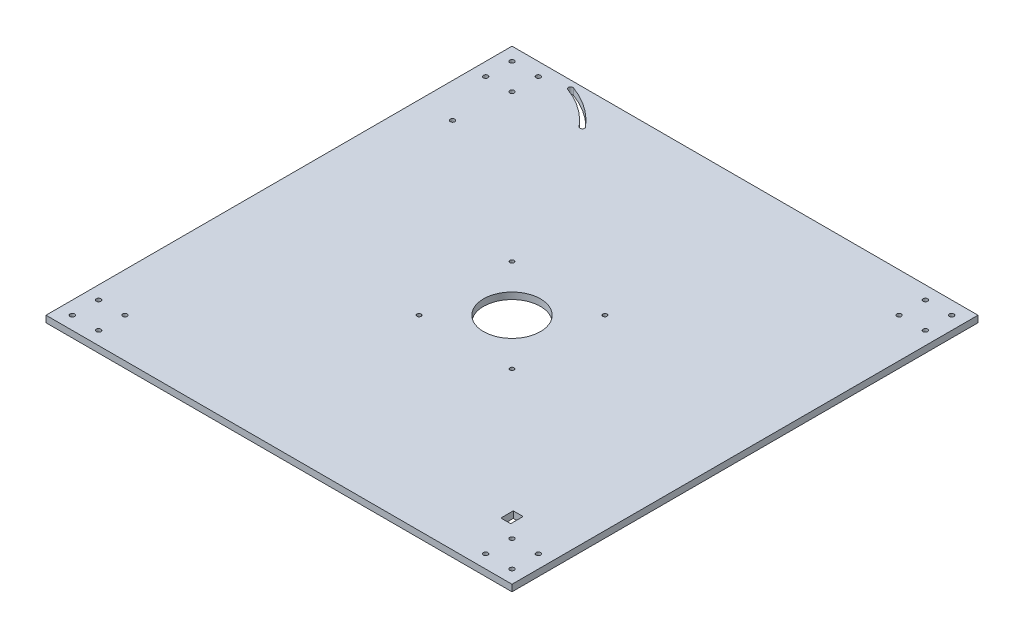
SolidWorks part; units mm, degrees
ref_plane "Front Plane" through (0, 0, 0) normal (0, 0, 1) x (1, 0, 0)
ref_plane "Top Plane" through (0, 0, 0) normal (0, 1, 0) x (1, 0, 0)
ref_plane "Right Plane" through (0, 0, 0) normal (1, 0, 0) x (0, 0, -1)
sketch "Sketch1" plane through (0, 0, 0) normal (0, 1, 0) x (1, 0, 0)
  line L1 (-224.79, -224.79) -> (224.79, -224.79)
  line L2 (-224.79, -224.79) -> (-224.79, 224.79)
  line L3 (-224.79, 224.79) -> (224.79, 224.79)
  line L4 (224.79, -224.79) -> (224.79, 224.79)
  line L5 (-224.79, -224.79) -> (224.79, 224.79) construction
  line L6 (-224.79, 224.79) -> (224.79, -224.79) construction
  point P0 (0, 0)
  dimension "D1" = 449.58
  dimension "D2" = 449.58
extrude "Boss-Extrude1" add sketch "Sketch1" along normal blind 6.35
sketch "Sketch2" plane through (0, 6.35, 0) normal (0, 1, 0) x (1, 0, 0)
  line L1 (-44.8437, -44.8437) -> (44.8437, -44.8437) construction
  line L2 (-44.8437, -44.8437) -> (-44.8437, 44.8437) construction
  line L3 (-44.8437, 44.8437) -> (44.8437, 44.8437) construction
  line L4 (44.8437, -44.8437) -> (44.8437, 44.8437) construction
  line L5 (-44.8437, -44.8437) -> (44.8437, 44.8437) construction
  line L6 (-44.8437, 44.8437) -> (44.8437, -44.8437) construction
  circle A0 centre (-44.8437, 44.8437) radius 1.9844
  circle A1 centre (44.8437, 44.8437) radius 1.9844
  circle A2 centre (-44.8437, -44.8437) radius 1.9844
  circle A3 centre (44.8437, -44.8437) radius 1.9844
  circle A4 centre (0, 0) radius 27.432
  point P0 (0, 0)
  dimension "D3" = 3.9688
  dimension "D4" = 54.864
  dimension "D1" = 89.6874
  dimension "D2" = 89.6874
extrude "Cut-Extrude1" cut sketch "Sketch2" against normal through all and the other way through all
sketch "Sketch3" plane through (0, 6.35, 0) normal (0, 1, 0) x (1, 0, 0)
  line L0 (173.5788, -162.8288) -> (164.0788, -174.8288) construction
  line L1 (0, 0) -> (224.79, -224.79) construction
  line L2 (164.0788, -162.8288) -> (173.5788, -174.8288) construction
  line L8 (164.0788, -174.8288) -> (173.5788, -174.8288)
  line L9 (164.0788, -174.8288) -> (164.0788, -162.8288)
  line L10 (164.0788, -162.8288) -> (173.5788, -162.8288)
  line L11 (173.5788, -174.8288) -> (173.5788, -162.8288)
  point P5 (168.8288, -168.8288)
  point P9 (168.8288, -168.8288)
  dimension "D1" = 238.76
  dimension "D2" = 9.5
  dimension "D3" = 12
extrude "Cut-Extrude2" cut sketch "Sketch3" against normal through all
sketch "Sketch4" plane through (0, 6.35, 0) normal (0, 1, 0) x (1, 0, 0)
  line L0 (224.79, 224.79) -> (-224.79, 224.79) construction
  line L1 (-199.39, 199.39) -> (199.39, 199.39) construction
  line L2 (-199.39, 199.39) -> (-199.39, -199.39) construction
  line L3 (-199.39, -199.39) -> (199.39, -199.39) construction
  line L4 (199.39, 199.39) -> (199.39, -199.39) construction
  line L5 (-199.39, 199.39) -> (199.39, -199.39) construction
  line L6 (-199.39, -199.39) -> (199.39, 199.39) construction
  line L7 (-224.79, 224.79) -> (-224.79, -224.79) construction
  line L9 (-212.09, 212.09) -> (-186.69, 212.09) construction
  line L10 (-212.09, 212.09) -> (-212.09, 186.69) construction
  line L11 (-212.09, 186.69) -> (-186.69, 186.69) construction
  line L12 (-186.69, 212.09) -> (-186.69, 186.69) construction
  line L13 (-212.09, 212.09) -> (-186.69, 186.69) construction
  line L14 (-212.09, 186.69) -> (-186.69, 212.09) construction
  line L15 (-212.09, -212.09) -> (-186.69, -212.09) construction
  line L16 (-212.09, -212.09) -> (-212.09, -186.69) construction
  line L17 (-212.09, -186.69) -> (-186.69, -186.69) construction
  line L18 (-186.69, -212.09) -> (-186.69, -186.69) construction
  line L19 (-212.09, -212.09) -> (-186.69, -186.69) construction
  line L20 (-212.09, -186.69) -> (-186.69, -212.09) construction
  line L21 (212.09, -212.09) -> (186.69, -212.09) construction
  line L22 (212.09, -212.09) -> (212.09, -186.69) construction
  line L23 (212.09, -186.69) -> (186.69, -186.69) construction
  line L24 (186.69, -212.09) -> (186.69, -186.69) construction
  line L25 (212.09, -212.09) -> (186.69, -186.69) construction
  line L26 (212.09, -186.69) -> (186.69, -212.09) construction
  line L27 (212.09, 212.09) -> (186.69, 212.09) construction
  line L28 (212.09, 212.09) -> (212.09, 186.69) construction
  line L29 (212.09, 186.69) -> (186.69, 186.69) construction
  line L30 (186.69, 212.09) -> (186.69, 186.69) construction
  line L31 (212.09, 212.09) -> (186.69, 186.69) construction
  line L32 (212.09, 186.69) -> (186.69, 212.09) construction
  circle A0 centre (-212.09, 212.09) radius 2.1828
  circle A1 centre (-186.69, 212.09) radius 2.1828
  circle A2 centre (-212.09, 186.69) radius 2.1828
  circle A3 centre (-186.69, 186.69) radius 2.1828
  circle A4 centre (186.69, 212.09) radius 2.1828
  circle A5 centre (186.69, 186.69) radius 2.1828
  circle A6 centre (212.09, 186.69) radius 2.1828
  circle A7 centre (212.09, 212.09) radius 2.1828
  circle A8 centre (186.69, -186.69) radius 2.1828
  circle A9 centre (212.09, -186.69) radius 2.1828
  circle A10 centre (212.09, -212.09) radius 2.1828
  circle A11 centre (186.69, -212.09) radius 2.1828
  circle A12 centre (-212.09, -186.69) radius 2.1828
  circle A13 centre (-186.69, -186.69) radius 2.1828
  circle A14 centre (-186.69, -212.09) radius 2.1828
  circle A15 centre (-212.09, -212.09) radius 2.1828
  point P0 (0, 0)
  dimension "D4" = 4.3656
  dimension "D1" = 25.4
  dimension "D2" = 25.4
  dimension "D3" = 25.4
extrude "Cut-Extrude3" cut sketch "Sketch4" against normal through all
sketch "Sketch5" plane through (0, 6.35, 0) normal (0, 1, 0) x (1, 0, 0)
  line L0 (0, 0) -> (-264.2421, 185.0243) construction
  line L1 (-123.3181, 191.1772) -> (-191.4194, 134.0333) construction
  line L2 (-161.0139, 217.572) -> (-191.4194, 134.0333) construction
  line L3 (0, 0) -> (0, 224.79) construction
  line L4 (224.79, 224.79) -> (-224.79, 224.79) construction
  circle A0 centre (-191.4194, 134.0333) radius 2.1828
  circle A1 centre (-191.4194, 134.0333) radius 88.9 construction
  arc A2 (-161.0139, 217.572) -> (-123.3181, 191.1772) centre (-191.4194, 134.0333) cw construction
  arc A3 (-121.646, 192.5802) -> (-160.2673, 219.6232) centre (-191.4194, 134.0333) ccw
  arc A4 (-124.9902, 189.7741) -> (-161.7604, 215.5208) centre (-191.4194, 134.0333) ccw
  arc A5 (-124.9902, 189.7741) -> (-121.646, 192.5802) centre (-123.3181, 191.1772) ccw
  arc A6 (-160.2673, 219.6232) -> (-161.7604, 215.5208) centre (-161.0139, 217.572) ccw
  point P7 (-140.4285, 206.856)
  dimension "D1" = 177.8
  dimension "D2" = 4.3656
  dimension "D3" = 30
  dimension "D6" = 2.1828
  dimension "D4" = 233.68
  dimension "D5" = 75
  dimension "D7" = 55
extrude "Cut-Extrude4" cut sketch "Sketch5" against normal through all
